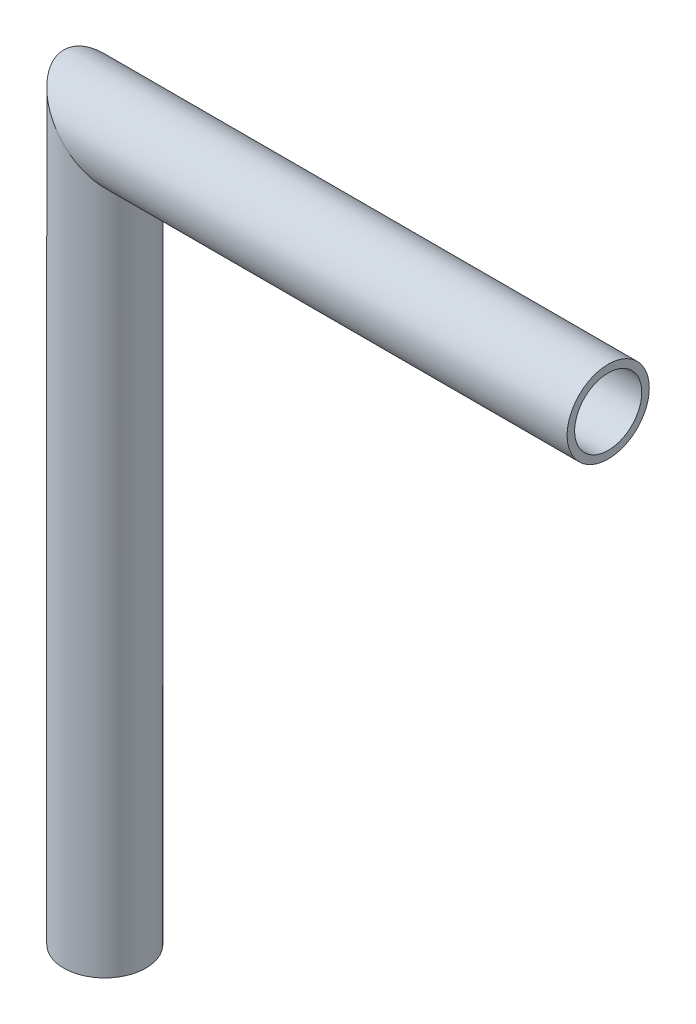
SolidWorks part; units mm, degrees
ref_plane "Front Plane" through (0, 0, 0) normal (0, 0, 1) x (1, 0, 0)
ref_plane "Top Plane" through (0, 0, 0) normal (0, 1, 0) x (1, 0, 0)
ref_plane "Right Plane" through (0, 0, 0) normal (1, 0, 0) x (0, 0, -1)
sketch "Sketch1" plane through (0, 0, 0) normal (0, 0, 1) x (1, 0, 0)
  line L0 (0, 0) -> (0, 170)
  line L1 (0, 170) -> (120, 170)
ref_plane "Plane1" through (120, 170, 0) normal (1, 0, 0) x (0, 0, -1)
sketch "Sketch2" plane through (120, 170, 0) normal (1, 0, 0) x (0, 0, -1)
  circle A0 centre (0, 0) radius 8
  circle A1 centre (0, 0) radius 9.7903
sweep "Sweep1" add profiles "Sketch2" path "Sketch1"
